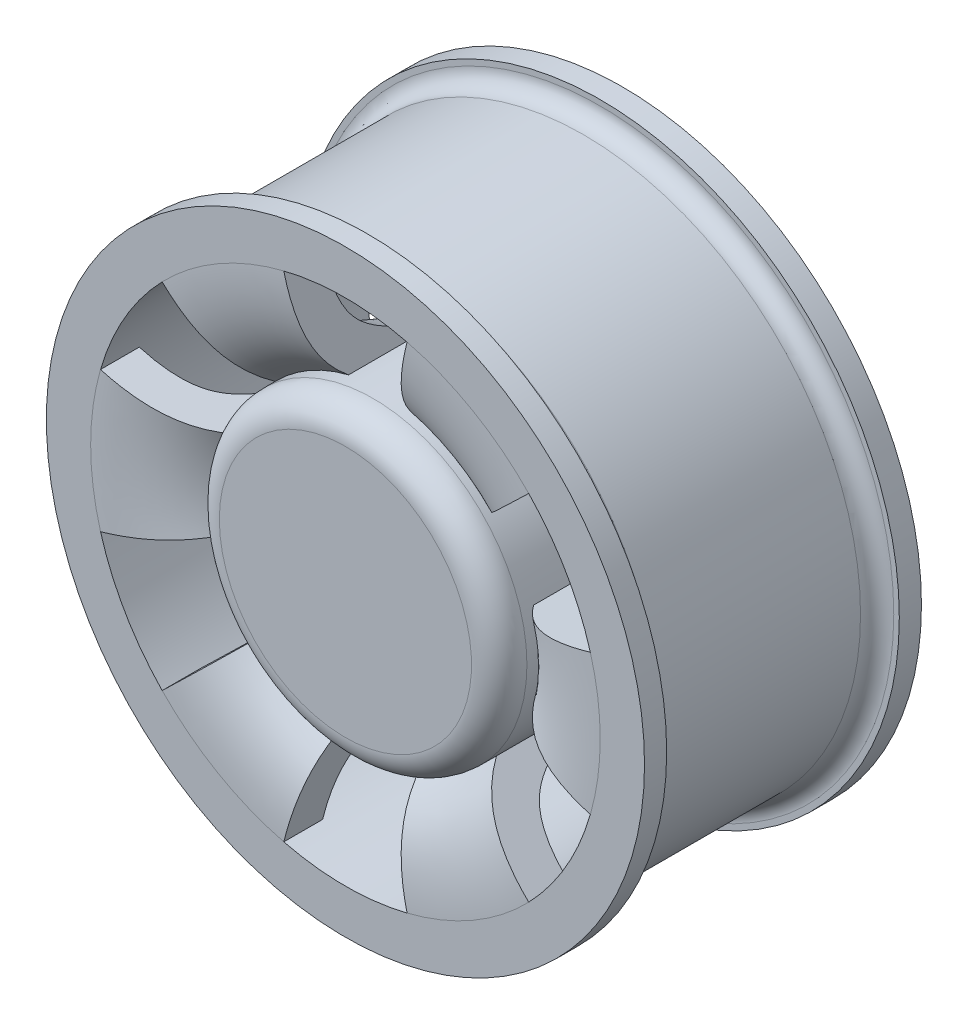
SolidWorks part; units mm, degrees
material "2024 Сплав"
ref_plane "Спереди" through (0, 0, 0) normal (0, 0, 1) x (1, 0, 0)
ref_plane "Сверху" through (0, 0, 0) normal (0, 1, 0) x (1, 0, 0)
ref_plane "Справа" through (0, 0, 0) normal (1, 0, 0) x (0, 0, -1)
sketch "Эскиз1" plane through (0, 0, 0) normal (0, 1, 0) x (1, 0, 0)
  line L0 (0, 0) -> (0, 47.4199) construction
  line L1 (0, 0) -> (79.812, 0) construction
  line L2 (46, 25) -> (46, -18)
  line L3 (46, -25) -> (54, -25)
  line L4 (54, -25) -> (54, -21)
  line L5 (54, -21) -> (53, -21)
  line L6 (50, -18) -> (50, 18)
  line L7 (54, 21) -> (53, 21)
  line L8 (54, 25) -> (54, 21)
  line L9 (46, 25) -> (54, 25)
  line L10 (40.0579, -25) -> (51.9421, -25) construction
  line L11 (20.5, 0) -> (27.7696, 0)
  arc A0 (53, -21) -> (50, -18) centre (53, -18) cw
  arc A1 (53, 21) -> (50, 18) centre (53, 18) ccw
  spline S0 degree 3 poles (46, -25) (27.8278, -25) (24.5333, -14.4961) (20.5, 0) knots 0 0 0 0 1 1 1 1
  spline S1 degree 1 poles (46, -18) (27.2438, 1.8764) knots 0 0 1 1 construction
  spline S2 degree 3 poles (46, -18) (45.5342, -18) (44.5772, -17.9825) (42.8692, -17.8825) (40.9712, -17.6453) (39.0897, -17.2169) (37.0322, -16.4976) (35.1527, -15.3982) (33.3638, -13.658) (31.6998, -11.1302) (30.4075, -8.2385) (29.4243, -5.4874) (28.7027, -3.2226) (28.1026, -1.1773) (27.6171, 0.5373) (27.3672, 1.4331) (27.2438, 1.8764) knots 0 0 0 0 0.03125 0.0625 0.125 0.1875 0.25 0.375 0.5 0.625 0.75 0.8125 0.875 0.9375 0.96875 1 1 1 1 only from (46, -18) to (27.7696, 0)
  point P3 (50, 21)
  point P12 (50, -21)
  point P16 (50, 0)
  point P19 (46, 0)
  dimension "D5" = 3
  dimension "D1" = 25
  dimension "D2" = 8
  dimension "D3" = 4
  dimension "D4" = 4
  dimension "D6" = 50
  dimension "D7" = 20.5
  dimension "D8" = 28
  dimension "D10" = 18
  dimension "D11" = 7.2696
  dimension "D9" = 7
revolve "Повернуть1" add sketch "Эскиз1" angle 360 about L0
sketch "Эскиз2" plane through (0, 0, 0) normal (0, 0, -1) x (-1, 0, 0)
  circle A0 centre (0, 0) radius 20.5 construction
  circle A1 centre (0, 0) radius 27.7695 construction
  circle A2 centre (0, 0) radius 20.5
  circle A3 centre (0, 0) radius 27.7695
extrude "Бобышка-Вытянуть1" add sketch "Эскиз2" against normal through all
sketch "Эскиз3" plane through (0, 0, 25) normal (0, 0, 1) x (1, 0, 0)
  circle A0 centre (0, 0) radius 27.7695 construction
  circle A1 centre (0, 0) radius 27.7695
extrude "Бобышка-Вытянуть2" add sketch "Эскиз3" against normal blind 5
sketch "Эскиз4" plane through (0, 0, 25) normal (0, 0, 1) x (1, 0, 0)
  line L0 (-6.7181, 26.9447) -> (-11.1284, 44.6336)
  line L1 (6.7181, 26.9447) -> (11.1284, 44.6336)
  circle A0 centre (0, 0) radius 27.7695 construction
  arc A1 (6.7181, 26.9447) -> (-6.7181, 26.9447) centre (0, 0) ccw
  circle A2 centre (0, 0) radius 46 construction
  arc A3 (11.1284, 44.6336) -> (-11.1284, 44.6336) centre (0, 0) ccw
  dimension "D1" = 28
extrude "Вырез-Вытянуть1" cut sketch "Эскиз4" against normal through all
pattern_circular "Круговой массив1" count 6 over 360 about axis through (0, 0, 0) along (0, 0, 1) of "Вырез-Вытянуть1"
fillet "Скругление1" radius 5 1 edges at (-27.7695, 0, 25)
sketch3d "Трехмерный эскиз1"
  line L0 (0, 0, 0) -> (-27.7695, 0, 0) construction
  arc A0 (-26.6938, 7.6543, 0) -> (-26.6938, -7.6543, 0) centre (0, 0, 0) ccw construction
  point P6 (0, 0, 27.7696)
  point P7 (-23.75, 0, 0)
  dimension "D1" = 23.75
hole_wizard "Сверление под метчик M51" positions "Эскиз11" profile "Эскиз13" hole size "M5" standard "ISO"
sketch "Эскиз11" plane through (0, 0, 0) normal (0, 0, -1) x (-1, 0, 0)
  point P0 (23.75, 0)
sketch "Эскиз13" plane through (-23.75, 0, 0) normal (1, 0, 0) x (0, 1, 0)
  line L0 (0, 0) -> (0, 23.2618)
  line L1 (0, 23.2618) -> (2.1, 22)
  line L2 (2.1, 22) -> (2.1, 0)
  line L5 (2.1, 0) -> (0, 0)
  line L10 (0, 23.2618) -> (-2.1, 22) construction
  line L11 (0, -6.35) -> (0, 107.95) construction
  dimension "Диаметр отверстия" = 4.2
  dimension "Глубина отверстия" = 22
  dimension "Угол заточки сверла" = 118
cosmetic thread "Условное изображение резьбы1" parameters "D2"=5
pattern_circular "Круговой массив3" count 6 over 360 about axis through (0, 0, 0) along (0, 0, 1) of "Сверление под метчик M51"
chamfer "Фаска2" distance 0.6 angle 45 6 edges at (-13.975, -20.5681, 0) (9.775, -20.5681, 0) (21.65, 0, 0) (9.775, 20.5681, 0) (-13.975, 20.5681, 0) (-25.85, 0, 0)
